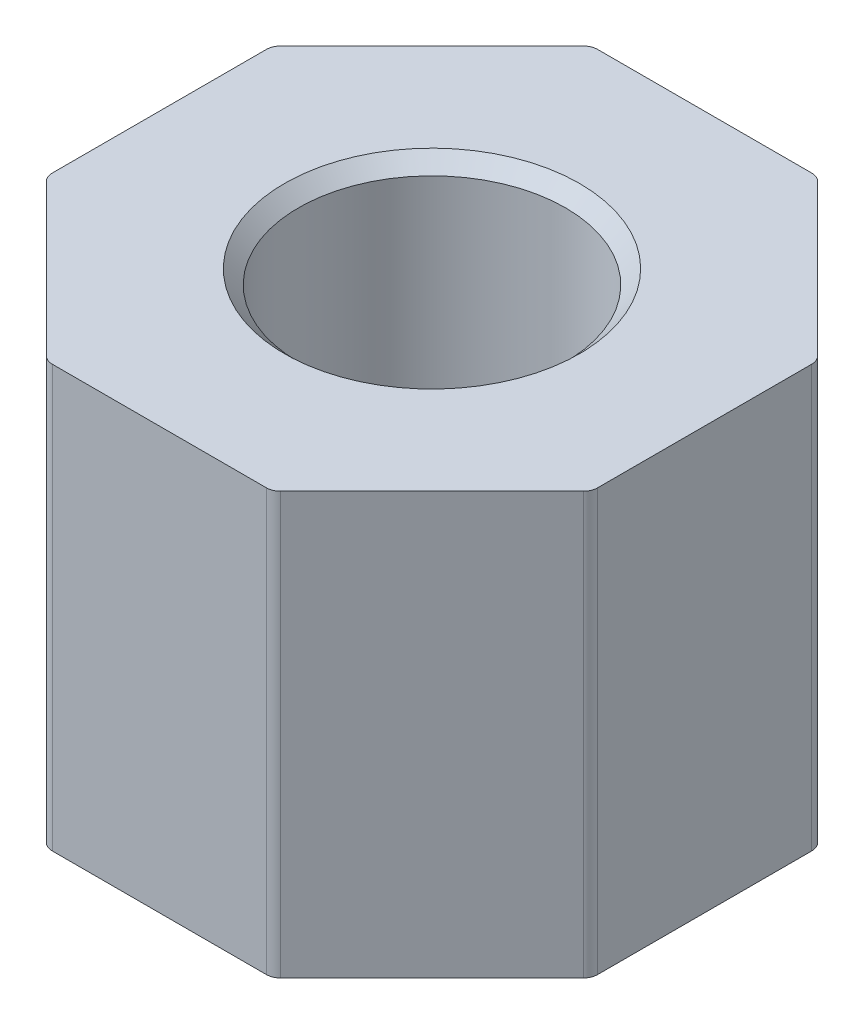
SolidWorks part; units mm, degrees
ref_plane "Piano frontale" through (0, 0, 0) normal (0, 0, 1) x (1, 0, 0)
ref_plane "Piano superiore" through (0, 0, 0) normal (0, 1, 0) x (1, 0, 0)
ref_plane "Piano destro" through (0, 0, 0) normal (1, 0, 0) x (0, 0, -1)
sketch "Schizzo1" plane through (0, 0, 0) normal (0, 1, 0) x (1, 0, 0)
  line L0 (-19.4015, 8.0364) -> (-8.0364, 19.4015)
  line L1 (-8.0364, 19.4015) -> (8.0364, 19.4015)
  line L2 (8.0364, 19.4015) -> (19.4015, 8.0364)
  line L3 (19.4015, 8.0364) -> (19.4015, -8.0364)
  line L4 (19.4015, -8.0364) -> (8.0364, -19.4015)
  line L5 (8.0364, -19.4015) -> (-8.0364, -19.4015)
  line L6 (-8.0364, -19.4015) -> (-19.4015, -8.0364)
  line L7 (-19.4015, -8.0364) -> (-19.4015, 8.0364)
  line L8 (-19.4015, 8.0364) -> (19.4015, 8.0364) construction
  line L9 (-19.4015, -8.0364) -> (19.4015, -8.0364) construction
  circle A1 centre (0, 0) radius 9.5
  circle A2 centre (0, 0) radius 21 construction
  point P13 (-19.4015, 0)
  point P14 (19.4015, 0)
  point P17 (0, 19.4015)
  point P20 (0, -19.4015)
  dimension "D1" = 19
  dimension "D2" = 42
extrude "Estrusione-Estrusione1" add sketch "Schizzo1" along normal blind 30
fillet "Raccordo1" radius 1 8 edges at (8.0364, 15, -19.4015) (19.4015, 15, -8.0364) (19.4015, 15, 8.0364) (8.0364, 15, 19.4015) (-8.0364, 15, 19.4015) (-19.4015, 15, 8.0364) (-8.0364, 15, -19.4015) (-19.4015, 15, -8.0364)
chamfer "Smusso1" distance 1 angle 45 2 edges at (0, 0, 9.5) (0, 30, 9.5)
